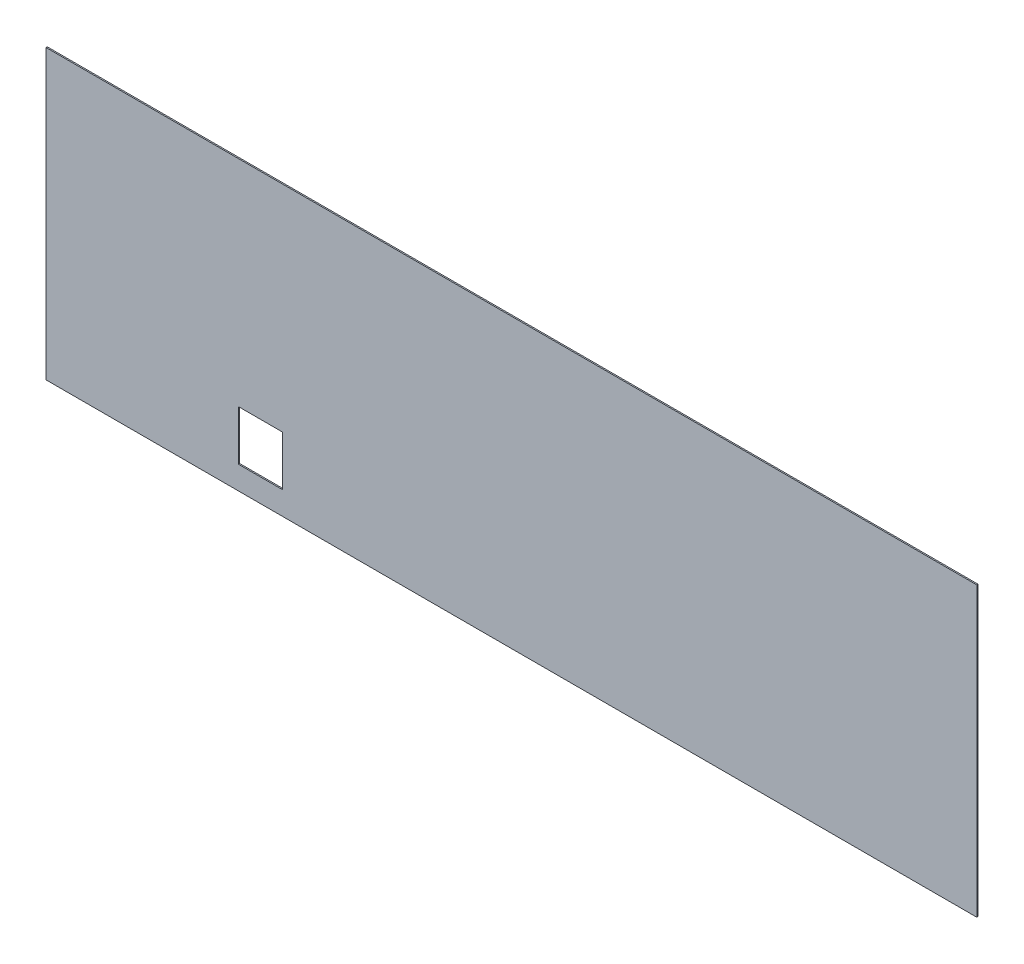
SolidWorks part; units mm, degrees
material "Chrome Stainless Steel"
ref_plane "Front Plane" through (0, 0, 0) normal (0, 0, 1) x (1, 0, 0)
ref_plane "Top Plane" through (0, 0, 0) normal (0, 1, 0) x (1, 0, 0)
ref_plane "Right Plane" through (0, 0, 0) normal (1, 0, 0) x (0, 0, -1)
sketch "Sketch1" plane through (0, 0, 0) normal (0, 0, 1) x (1, 0, 0)
  line L1 (0, 0) -> (747, 0)
  line L2 (0, 0) -> (0, 231)
  line L3 (0, 231) -> (747, 231)
  line L4 (747, 0) -> (747, 231)
extrude "Boss-Extrude1" add sketch "Sketch1" along normal blind 1
sketch "Sketch2" plane through (0, 0, 0) normal (0, 0, -1) x (-1, 0, 0)
  line L1 (-189.7625, 58.6219) -> (-154.3801, 58.6219)
  line L2 (-189.7625, 58.6219) -> (-189.7625, 18.5804)
  line L3 (-189.7625, 18.5804) -> (-154.3801, 18.5804)
  line L4 (-154.3801, 58.6219) -> (-154.3801, 18.5804)
extrude "Cut-Extrude1" cut sketch "Sketch2" against normal blind 10
